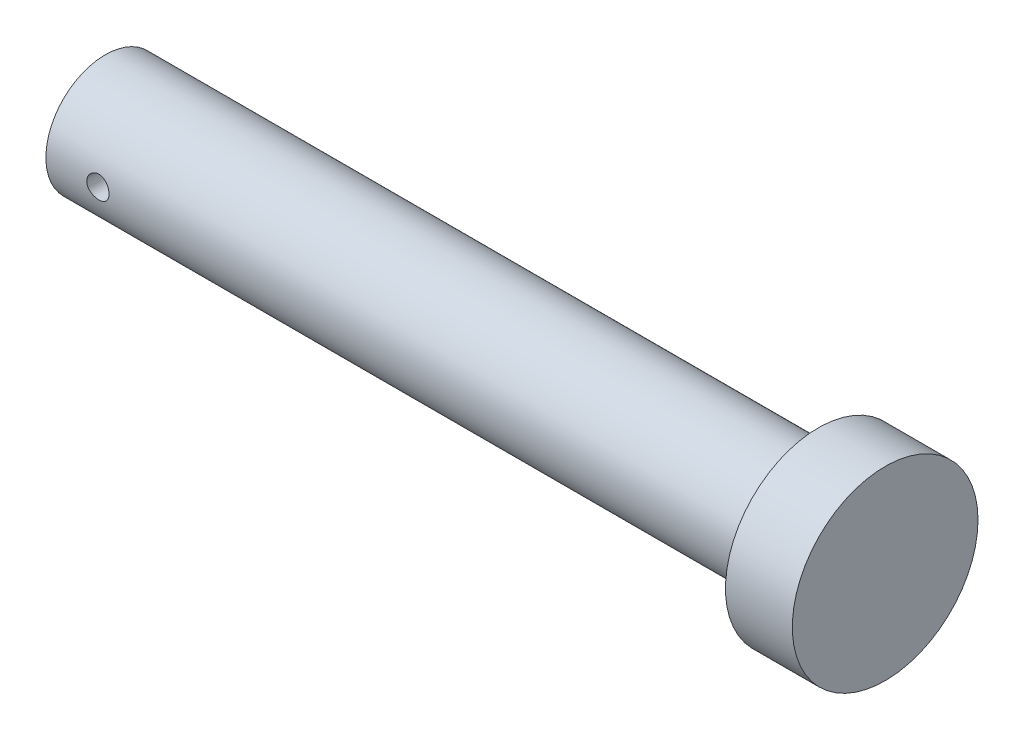
SolidWorks part; units mm, degrees
ref_plane "Front Plane" through (0, 0, 0) normal (0, 0, 1) x (1, 0, 0)
ref_plane "Top Plane" through (0, 0, 0) normal (0, 1, 0) x (1, 0, 0)
ref_plane "Right Plane" through (0, 0, 0) normal (1, 0, 0) x (0, 0, -1)
sketch "Sketch1" plane through (0, 0, 0) normal (1, 0, 0) x (0, 0, -1)
  circle A0 centre (0, 0) radius 8
  dimension "D1" = 16
extrude "Boss-Extrude1" add sketch "Sketch1" along normal blind 96
sketch "Sketch4" plane through (96, 0, 0) normal (1, 0, 0) x (0, 0, -1)
  circle A0 centre (0, 0) radius 12.5
  dimension "D1" = 25
extrude "Boss-Extrude2" add sketch "Sketch4" along normal blind 9
sketch "Sketch5" plane through (0, 0, 0) normal (0, 0, 1) x (1, 0, 0)
  line L0 (96, -12.5) -> (105, -12.5) construction
  line L1 (105, 12.5) -> (96, 12.5) construction
  line L2 (105, -12.5) -> (105, 12.5) construction
  line L3 (96, 12.5) -> (96, -12.5) construction
  line L4 (0, -8) -> (96, -8) construction
  line L5 (96, 8) -> (0, 8) construction
  line L6 (0, 8) -> (0, -8) construction
  line L7 (96, -12.5) -> (105, -12.5)
  line L8 (105, 12.5) -> (96, 12.5)
  line L9 (105, -12.5) -> (105, 12.5)
  line L10 (96, 12.5) -> (96, -12.5)
  line L11 (0, -8) -> (96, -8)
  line L12 (96, 8) -> (0, 8)
  line L13 (0, 8) -> (0, -8)
  circle A0 centre (7, 0) radius 1.5
  dimension "D2" = 3
  dimension "D1" = 89
extrude "Cut-Extrude1" cut sketch "Sketch5" against normal through all both and the other way through all contours A0
